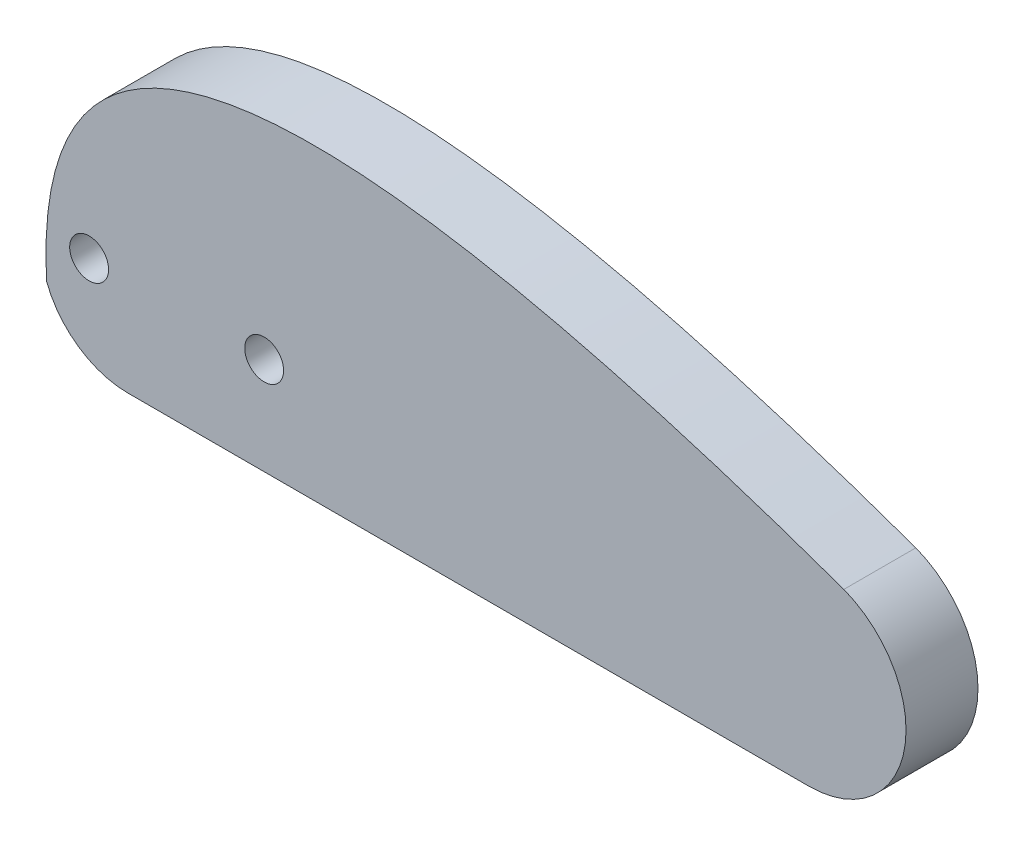
SolidWorks part; units mm, degrees
ref_plane "Front Plane" through (0, 0, 0) normal (0, 0, 1) x (1, 0, 0)
ref_plane "Top Plane" through (0, 0, 0) normal (0, 1, 0) x (1, 0, 0)
ref_plane "Right Plane" through (0, 0, 0) normal (1, 0, 0) x (0, 0, -1)
sketch "Sketch1" plane through (0, 0, 0) normal (0, 0, 1) x (1, 0, 0)
  line L0 (0, 0) -> (35, 0) construction
  line L2 (0, -5) -> (35, -5)
  arc A1 (35, -5) -> (36.8029, 4.6637) centre (35, 0) ccw
  circle A2 centre (-2, 0) radius 1
  circle A3 centre (7, 0) radius 1
  arc A5 (0, -5) -> (-4.1829, -2.1312) centre (0, -0.5161) cw
  spline S0 degree 2 poles (-4.1829, -2.1312) (-5.4225, 19.7412) (36.8029, 4.6637) knots 0 0 0 1 1 1
  point P3 (17.5, 0)
  point P8 (-3, 0)
  dimension "D4" = 2
  dimension "D2" = 5
  dimension "D7" = 4.4839
  dimension "D12" = 5
  dimension "D1" = 35
  dimension "D3" = 35
  dimension "D5" = 19.5
  dimension "D6" = 9
  dimension "D8" = 41.021
  dimension "D9" = 7
  dimension "D10" = 2
  dimension "D11" = 35
  dimension "D13" = 4.2182
extrude "Boss-Extrude1" add sketch "Sketch1" along normal blind 3.7
